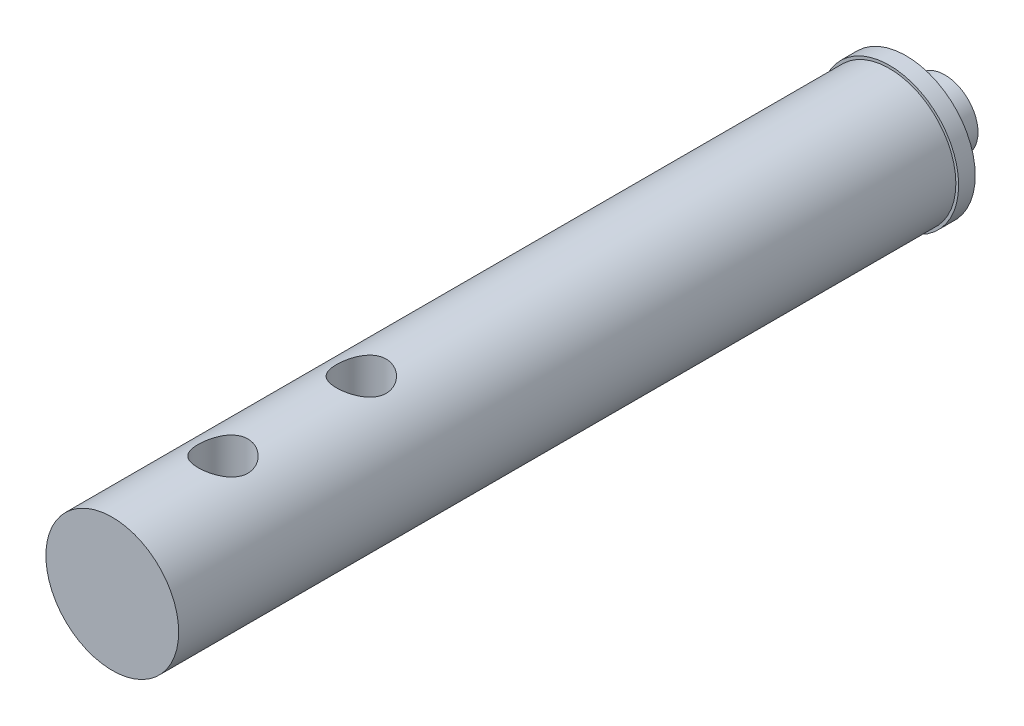
SolidWorks part; units mm, degrees
material "Galvanized Steel"
ref_plane "Front Plane" through (0, 0, 0) normal (0, 0, 1) x (1, 0, 0)
ref_plane "Top Plane" through (0, 0, 0) normal (0, 1, 0) x (1, 0, 0)
ref_plane "Right Plane" through (0, 0, 0) normal (1, 0, 0) x (0, 0, -1)
sketch "Sketch1" plane through (0, 0, 0) normal (0, 0, 1) x (1, 0, 0)
  circle A0 centre (0, 0) radius 6
  dimension "D1" = 12
extrude "Boss-Extrude1" add sketch "Sketch1" along normal blind 7
sketch "Sketch2" plane through (0, 0, 7) normal (0, 0, 1) x (1, 0, 0)
  circle A0 centre (0, 0) radius 12.5
  dimension "D1" = 25
extrude "Boss-Extrude2" add sketch "Sketch2" along normal blind 3
sketch "Sketch3" plane through (0, 0, 10) normal (0, 0, 1) x (1, 0, 0)
  circle A0 centre (0, 0) radius 12
  dimension "D1" = 24
extrude "Boss-Extrude3" add sketch "Sketch3" along normal blind 140.45
sketch "Sketch4" plane through (0, 0, 0) normal (0, 1, 0) x (1, 0, 0)
  line L0 (-12, -150.45) -> (12, -150.45) construction
  circle A0 centre (0, -130.45) radius 4.5
  dimension "D1" = 9
  dimension "D2" = 20
extrude "Cut-Extrude1" cut sketch "Sketch4" against normal through all both and the other way through all
pattern_linear "LPattern1" count 2 spacing 25 along (0, 0, -1) of "Cut-Extrude1"
